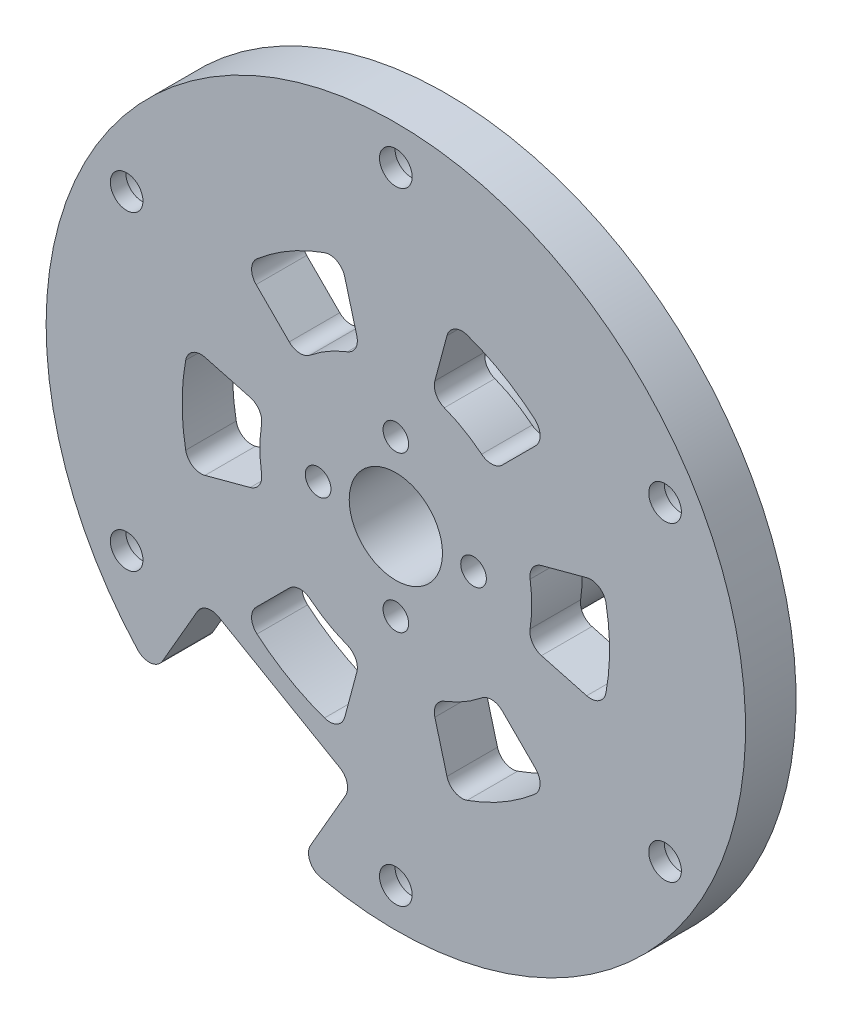
SolidWorks part; units mm, degrees
material "6061 合金"
ref_plane "前视基准面" through (0, 0, 0) normal (0, 0, 1) x (1, 0, 0)
ref_plane "上视基准面" through (0, 0, 0) normal (0, 1, 0) x (1, 0, 0)
ref_plane "右视基准面" through (0, 0, 0) normal (1, 0, 0) x (0, 0, -1)
other "Configuration Table"
sketch "草图1" plane through (0, 0, 0) normal (0, 0, 1) x (1, 0, 0)
  circle A0 centre (0, 0) radius 45
  dimension "D1" = 90
extrude "凸台-拉伸1" add sketch "草图1" along normal blind 6
sketch "草图2" plane through (0, 0, 6) normal (0, 0, 1) x (1, 0, 0)
  circle A0 centre (0, 0) radius 34.65
  circle A1 centre (0, 0) radius 40 construction
  circle A2 centre (0, 40) radius 2
  circle A3 centre (34.641, 20) radius 2
  circle A4 centre (34.641, -20) radius 2
  circle A5 centre (0, -40) radius 2
  circle A6 centre (-34.641, -20) radius 2
  circle A7 centre (-34.641, 20) radius 2
  point P18 (0, 0)
  dimension "D1" = 69.3
  dimension "D2" = 80
  dimension "D3" = 4
  dimension "D4" = 6
extrude "切除-拉伸1" cut sketch "草图2" against normal through all
sketch "草图4" plane through (0, 0, 0) normal (0, 0, -1) x (-1, 0, 0)
  circle A0 centre (0, 0) radius 34.65
  dimension "D1" = 69.3
extrude "凸台-拉伸3" add sketch "草图4" against normal blind 3.5
sketch "草图5" plane through (0, 0, 0) normal (0, 0, -1) x (-1, 0, 0)
  circle A1 centre (0, 0) radius 15
  dimension "D2" = 30
extrude "凸台-拉伸4" add sketch "草图5" along normal blind 17
sketch "草图6" plane through (0, 0, 0) normal (0, 0, -1) x (-1, 0, 0)
  circle A0 centre (0, 40) radius 3.75
  dimension "D1" = 7.5
extrude "切除-拉伸2" cut sketch "草图6" against normal blind 4
pattern_circular "阵列(圆周)1" count 6 over 360 about axis through (0, 0, 0) along (0, 0, 1) of "切除-拉伸2"
sketch "草图9" plane through (0, 0, 0) normal (0, 0, -1) x (-1, 0, 0)
  line L0 (0, 0) -> (-26.7436, 46.3213) construction
  line L1 (0, 0) -> (0, 68.3893) construction
  line L13 (24.5263, -20.4808) -> (42.0263, -50.7917)
  line L14 (24.5263, -20.4808) -> (5.4737, -31.4808)
  line L15 (42.0263, -50.7917) -> (22.9737, -61.7917)
  line L16 (5.4737, -31.4808) -> (22.9737, -61.7917)
  line L17 (24.5263, -20.4808) -> (22.9737, -61.7917) construction
  line L18 (42.0263, -50.7917) -> (5.4737, -31.4808) construction
  point P12 (23.75, -41.1362)
  dimension "D1" = 30
  dimension "D4" = 22
  dimension "D5" = 35
  dimension "D6" = 30
extrude "切除-拉伸4" cut sketch "草图9" against normal through all
sketch "草图11" plane through (0, 0, 6) normal (0, 0, 1) x (1, 0, 0)
  line L2 (-31.3437, -32.2889) -> (-25.9551, -22.9555)
  line L3 (-6.9025, -33.9555) -> (-12.2911, -43.2889)
  line L4 (-31.3437, -32.2889) -> (-25.9551, -22.9555)
  line L5 (-6.9025, -33.9555) -> (-12.2911, -43.2889)
  arc A2 (-6.9025, -33.9555) -> (-25.9551, -22.9555) centre (0, 0) ccw
  arc A3 (-12.2911, -43.2889) -> (-31.3437, -32.2889) centre (0, 0) ccw
  arc A4 (-6.9025, -33.9555) -> (-25.9551, -22.9555) centre (0, 0) ccw
  arc A5 (-12.2911, -43.2889) -> (-31.3437, -32.2889) centre (0, 0) ccw
  dimension "D1" = 0
extrude "切除-拉伸5" cut sketch "草图11" against normal blind 2.5
sketch "草图12" plane through (0, 0, 3.5) normal (0, 0, 1) x (1, 0, 0)
  line L3 (-5.4737, -31.4808) -> (-12.2911, -43.2889)
  line L4 (-31.3437, -32.2889) -> (-24.5263, -20.4808)
  line L5 (-24.5263, -20.4808) -> (-5.4737, -31.4808)
  line L6 (-5.4737, -31.4808) -> (-12.2911, -43.2889)
  line L7 (-31.3437, -32.2889) -> (-24.5263, -20.4808)
  line L8 (-24.5263, -20.4808) -> (-5.4737, -31.4808)
  arc A1 (-12.2911, -43.2889) -> (-31.3437, -32.2889) centre (0, 0) ccw
  arc A2 (-12.2911, -43.2889) -> (-31.3437, -32.2889) centre (0, 0) ccw
  dimension "D1" = 0
extrude "凸台-拉伸6" add sketch "草图12" along normal blind 3
sketch "草图13" plane through (0, 0, 6.5) normal (0, 0, 1) x (1, 0, 0)
  circle A0 centre (0, 40) radius 2.1
  circle A1 centre (34.641, 20) radius 2.1
  circle A2 centre (34.641, -20) radius 2.1
  circle A3 centre (0, -40) radius 2.1
  circle A4 centre (-34.641, -20) radius 2.1
  circle A5 centre (-34.641, 20) radius 2.1
  point P16 (0, 0)
  dimension "D1" = 4.2
  dimension "D2" = 6
extrude "切除-拉伸6" cut sketch "草图13" against normal blind 5
sketch "草图14" plane through (0, 0, 3.5) normal (0, 0, -1) x (-1, 0, 0)
  circle A0 centre (34.641, 20) radius 3.75 construction
  circle A1 centre (0, 40) radius 3.75
  circle A2 centre (0, 40) radius 3.75
  circle A3 centre (-34.641, 20) radius 3.75
  circle A4 centre (-34.641, 20) radius 3.75
  circle A5 centre (34.641, -20) radius 3.75 construction
  circle A6 centre (0, -40) radius 3.75 construction
  circle A7 centre (-34.641, -20) radius 3.75 construction
  circle A8 centre (34.641, 20) radius 3.75
  circle A9 centre (34.641, -20) radius 3.75
  circle A10 centre (0, -40) radius 3.75
  circle A11 centre (-34.641, -20) radius 3.75
  dimension "D1" = 0
  dimension "D2" = 0
extrude "切除-拉伸7" cut sketch "草图14" against normal blind 1
sketch "草图18" plane through (0, 0, -17) normal (0, 0, -1) x (-1, 0, 0)
  circle A0 centre (0, 0) radius 10 construction
  circle A1 centre (0, 10) radius 2
  circle A2 centre (10, 0) radius 2
  circle A3 centre (0, -10) radius 2
  circle A4 centre (-10, 0) radius 2
  point P14 (0, 0)
  dimension "D1" = 20
  dimension "D3" = 4
  dimension "D2" = 4
hole_wizard "M4 螺纹孔1" positions "3D草图1" profile "草图19" tap size "M4" standard "GB" end condition through all
sketch3d "3D草图1"
  point P0 (0, 10, -17)
  point P3 (-10, 0, -17)
  point P6 (0, -10, -17)
  point P9 (10, 0, -17)
sketch "草图19" plane through (0, 10, -17) normal (1, 0, 0) x (0, 1, 0)
  line L0 (0, 0) -> (0, 23.5)
  line L1 (0, 23.5) -> (1.65, 23.5)
  line L2 (1.65, 23.5) -> (1.65, 0)
  line L5 (1.65, 0) -> (0, 0)
  line L11 (0, -6.35) -> (0, 107.95) construction
  dimension "通孔螺纹孔钻头直径" = 3.3
  dimension "通孔螺纹孔钻头深度" = 23.5
cosmetic thread "孔螺蚊线1" parameters "D2"=4
cosmetic thread "孔螺蚊线2" parameters "D2"=4
cosmetic thread "孔螺蚊线3" parameters "D2"=4
cosmetic thread "孔螺蚊线4" parameters "D2"=4
fillet "圆角1" radius 2 4 edges at (-24.5263, -20.4808, 3.25) (-31.3437, -32.2889, 3.25) (-5.4737, -31.4808, 3.25) (-12.2911, -43.2889, 3.25)
sketch "草图20" plane through (0, 0, 0) normal (0, 0, -1) x (-1, 0, 0)
  line L0 (-4.5293, 16.9037) -> (-7.1175, 26.563)
  line L2 (-19.4454, 19.4454) -> (-12.3744, 12.3744)
  line L3 (0, 40) -> (0, 0) construction
  line L4 (12.3744, 12.3744) -> (19.4454, 19.4454)
  line L5 (7.1175, 26.563) -> (4.5293, 16.9037)
  line L6 (16.9037, -4.5293) -> (26.563, -7.1175)
  line L7 (26.563, 7.1175) -> (16.9037, 4.5293)
  line L8 (4.5293, -16.9037) -> (7.1175, -26.563)
  line L9 (19.4454, -19.4454) -> (12.3744, -12.3744)
  line L10 (-12.3744, -12.3744) -> (-19.4454, -19.4454)
  line L11 (-7.1175, -26.563) -> (-4.5293, -16.9037)
  line L12 (-16.9037, 4.5293) -> (-26.563, 7.1175)
  line L13 (-26.563, -7.1175) -> (-16.9037, -4.5293)
  arc A0 (-4.5293, 16.9037) -> (-12.3744, 12.3744) centre (0, 0) ccw
  arc A1 (-7.1175, 26.563) -> (-19.4454, 19.4454) centre (0, 0) ccw
  arc A2 (19.4454, 19.4454) -> (7.1175, 26.563) centre (0, 0) ccw
  arc A3 (12.3744, 12.3744) -> (4.5293, 16.9037) centre (0, 0) ccw
  arc A4 (26.563, -7.1175) -> (26.563, 7.1175) centre (0, 0) ccw
  arc A5 (16.9037, -4.5293) -> (16.9037, 4.5293) centre (0, 0) ccw
  arc A6 (7.1175, -26.563) -> (19.4454, -19.4454) centre (0, 0) ccw
  arc A7 (4.5293, -16.9037) -> (12.3744, -12.3744) centre (0, 0) ccw
  arc A8 (-19.4454, -19.4454) -> (-7.1175, -26.563) centre (0, 0) ccw
  arc A9 (-12.3744, -12.3744) -> (-4.5293, -16.9037) centre (0, 0) ccw
  arc A10 (-26.563, 7.1175) -> (-26.563, -7.1175) centre (0, 0) ccw
  arc A11 (-16.9037, 4.5293) -> (-16.9037, -4.5293) centre (0, 0) ccw
  point P30 (0, 0)
  dimension "D1" = 55
  dimension "D2" = 35
  dimension "D3" = 30
  dimension "D4" = 10
  dimension "D5" = 10
  dimension "D6" = 45
  dimension "D7" = 6
extrude "切除-拉伸8" cut sketch "草图20" against normal blind 10
fillet "圆角2" radius 2 24 edges at (16.9037, -4.5293, 3.25) (26.563, -7.1175, 3.25) (26.563, 7.1175, 3.25) (16.9037, 4.5293, 3.25) (4.5293, -16.9037, 3.25) (7.1175, -26.563, 3.25) (19.4454, -19.4454, 3.25) (12.3744, -12.3744, 3.25) (-12.3744, -12.3744, 3.25) (-19.4454, -19.4454, 3.25) (-7.1175, -26.563, 3.25) (-4.5293, -16.9037, 3.25) (-16.9037, 4.5293, 3.25) (-26.563, 7.1175, 3.25) (-26.563, -7.1175, 3.25) (-16.9037, -4.5293, 3.25) (-4.5293, 16.9037, 3.25) (-19.4454, 19.4454, 3.25) (-12.3744, 12.3744, 3.25) (-7.1175, 26.563, 3.25) (12.3744, 12.3744, 3.25) (7.1175, 26.563, 3.25) (4.5293, 16.9037, 3.25) (19.4454, 19.4454, 3.25)
sketch "草图21" plane through (0, 0, -17) normal (0, 0, -1) x (-1, 0, 0)
  circle A0 centre (0, 0) radius 6
  dimension "D1" = 12
extrude "切除-拉伸9" cut sketch "草图21" against normal blind 68
